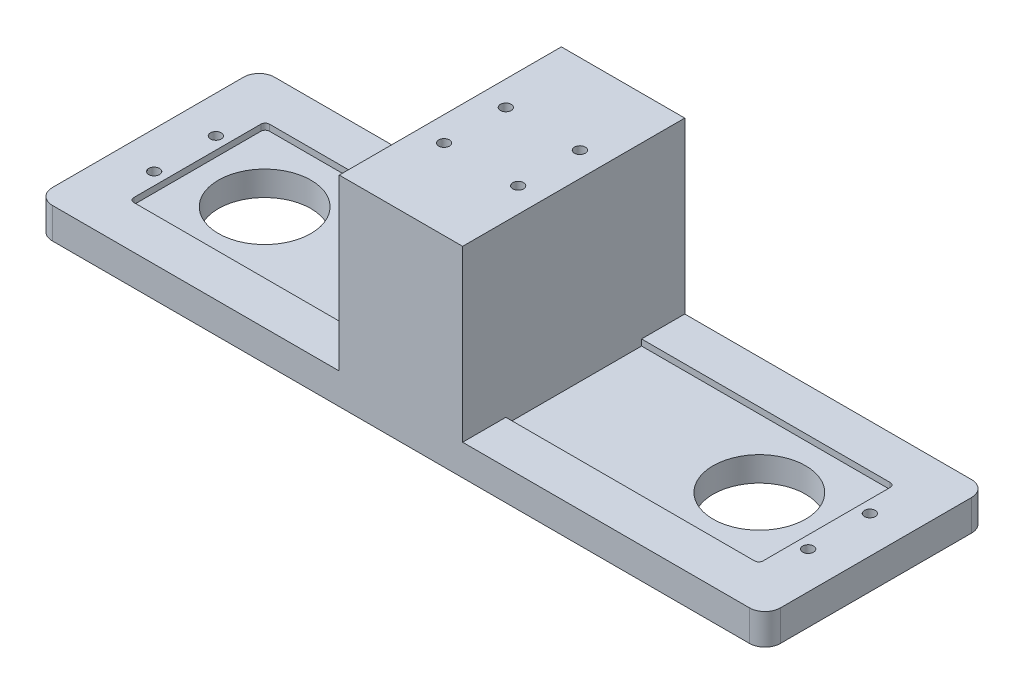
SolidWorks part; units mm, degrees
ref_plane "Front Plane" through (0, 0, 0) normal (0, 0, 1) x (1, 0, 0)
ref_plane "Top Plane" through (0, 0, 0) normal (0, 1, 0) x (1, 0, 0)
ref_plane "Right Plane" through (0, 0, 0) normal (1, 0, 0) x (0, 0, -1)
sketch "Sketch1" plane through (0, 0, 0) normal (0, 1, 0) x (1, 0, 0)
  line L0 (-90.7115, 0) -> (107.9024, 0) construction
  line L1 (56.5, 18) -> (-56.5, 18)
  line L2 (59, 15.5) -> (59, -15.5)
  line L3 (56.5, -18) -> (-56.5, -18)
  line L4 (-59, 15.5) -> (-59, -15.5)
  line L5 (59, 18) -> (-59, -18) construction
  line L6 (59, -18) -> (-59, 18) construction
  line L7 (0, 80.3055) -> (0, -51.0584) construction
  line L8 (-10, 18) -> (-10, -18)
  line L9 (10, 18) -> (10, -18)
  arc A0 (59, -15.5) -> (56.5, -18) centre (56.5, -15.5) cw
  arc A1 (56.5, 18) -> (59, 15.5) centre (56.5, 15.5) cw
  arc A2 (-56.5, 18) -> (-59, 15.5) centre (-56.5, 15.5) ccw
  arc A3 (-56.5, -18) -> (-59, -15.5) centre (-56.5, -15.5) cw
  point P0 (0, 0)
  dimension "D4" = 2.5
  dimension "D1" = 59
  dimension "D2" = 36
  dimension "D3" = 10
extrude "Boss-Extrude1" add sketch "Sketch1" along normal blind 4 contours A3 L3 L8 L1 A2 L4 | L9 L1 L8 L3 | A1 L1 L9 L3 A0 L2
sketch "Sketch2" plane through (0, 4, 0) normal (0, 1, 0) x (1, 0, 0)
  line L0 (-10, 18) -> (-10, -18)
  line L1 (-10, -18) -> (10, -18)
  line L2 (10, -18) -> (10, 18)
  line L3 (10, 18) -> (-10, 18)
extrude "Boss-Extrude2" add sketch "Sketch2" along normal blind 28.5
sketch "Sketch7" plane through (0, 4, 0) normal (0, 1, 0) x (1, 0, 0)
  line L0 (-61.3938, 0) -> (26.8477, 0) construction
  line L1 (-51, 11) -> (-10, 11)
  line L2 (-51, 11) -> (-51, -11)
  line L3 (-51, -11) -> (-10, -11)
  line L5 (-59, 15.5) -> (-59, -15.5) construction
  line L7 (-10, 18) -> (-56.5, 18) construction
  line L8 (-10, 18) -> (-56.5, 18)
  line L9 (-59, 15.5) -> (-59, -15.5)
  line L10 (-10, -18) -> (-56.5, -18) construction
  line L11 (-10, -18) -> (-56.5, -18)
  line L12 (-10, 18) -> (-10, -18) construction
  line L13 (-10, 18) -> (-10, 11)
  line L14 (-10, -11) -> (-10, -18)
  arc A0 (-56.5, 18) -> (-59, 15.5) centre (-56.5, 15.5) ccw construction
  arc A1 (-56.5, 18) -> (-59, 15.5) centre (-56.5, 15.5) ccw
  arc A2 (-59, -15.5) -> (-56.5, -18) centre (-56.5, -15.5) ccw construction
  arc A3 (-59, -15.5) -> (-56.5, -18) centre (-56.5, -15.5) ccw
  dimension "D1" = 8
  dimension "D3" = 22
extrude "Boss-Extrude3" add sketch "Sketch7" along normal blind 1
fillet "Fillet1" radius 0.7 1 edges at (-51, 4.5, -11)
fillet "Fillet3" radius 0.7 1 edges at (-51, 4.5, 11)
mirror "Mirror3" about plane through (0, 0, 0) normal (1, 0, 0) of "Boss-Extrude3", "Fillet3"
fillet "Fillet4" radius 0.7 1 edges at (51, 4.5, -11)
sketch "Sketch14" plane through (0, 5, 0) normal (0, 1, 0) x (1, 0, 0)
  line L0 (-56.5, -18) -> (-10, -18) construction
  line L1 (-59, 15.5) -> (-59, -15.5) construction
  line L2 (0, 23.8061) -> (0, 18) construction
  line L3 (10, 18) -> (-10, 18) construction
  line L4 (0, -27.9367) -> (0, 24.5607) construction
  circle A0 centre (-53, -5) radius 0.875
  circle A1 centre (-53, 5) radius 0.875
  circle A2 centre (53, -5) radius 0.875
  circle A3 centre (53, 5) radius 0.875
  dimension "D1" = 1.75
  dimension "D2" = 1.75
  dimension "D3" = 10
  dimension "D4" = 13
  dimension "D5" = 6
extrude "Cut-Extrude3" cut sketch "Sketch14" against normal through all
sketch "Sketch16" plane through (0, 0, 0) normal (0, -1, 0) x (1, 0, 0)
  line L0 (-59, -15.5) -> (-59, 14.0872)
  line L1 (-59, -15.5) -> (-59, 15.5) construction
  line L2 (56.5, 18) -> (-56.5, 18) construction
  line L3 (-53.3188, 18) -> (-29.2619, 18)
  circle A0 centre (-40.09, 0) radius 7.5
  dimension "D3" = 15
  dimension "D1" = 18.91
  dimension "D2" = 18
extrude "Cut-Extrude4" cut sketch "Sketch16" against normal blind 10 contours A0
ref_plane "Plane1" through (0, 0, 0) normal (-1, 0, 0) x (0, 0, 1)
mirror "Mirror4" about plane through (0, 0, 0) normal (-1, 0, 0) of "Cut-Extrude4"
sketch "Sketch17" plane through (0, 32.5, 0) normal (0, 1, 0) x (1, 0, 0)
  line L0 (0, 0) -> (0, -5)
  line L1 (0, 15.675) -> (0, -15.675) construction
sketch "Sketch18" plane through (0, 32.5, 0) normal (0, 1, 0) x (1, 0, 0)
  line L0 (0, 0) -> (0, -5)
  line L1 (0, -5) -> (-6, -5)
  line L2 (0, 0) -> (0, 5)
  line L3 (0, 15.675) -> (0, -15.675) construction
  line L4 (0, 5) -> (-6, 5)
  circle A0 centre (-6, -5) radius 0.875
  circle A1 centre (-6, 5) radius 0.875
  circle A2 centre (6, 5) radius 0.875
  circle A3 centre (6, -5) radius 0.875
  dimension "D2" = 1.75
  dimension "D6" = 1.75
  dimension "D7" = 1.75
  dimension "D8" = 1.75
  dimension "D1" = 6
  dimension "D3" = 10
  dimension "D4" = 10
  dimension "D5" = 6
  dimension "D9" = 6
  dimension "D10" = 6
extrude "Cut-Extrude5" cut sketch "Sketch18" against normal blind 10
